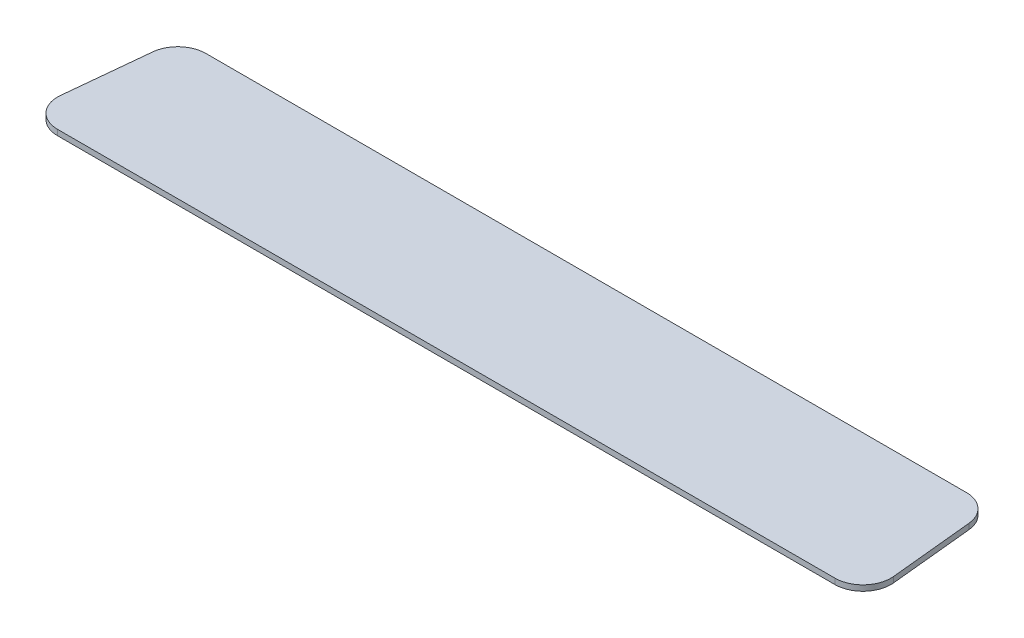
SolidWorks part; units mm, degrees
ref_plane "Front Plane" through (0, 0, 0) normal (0, 0, 1) x (1, 0, 0)
ref_plane "Top Plane" through (0, 0, 0) normal (0, 1, 0) x (1, 0, 0)
ref_plane "Right Plane" through (0, 0, 0) normal (1, 0, 0) x (0, 0, -1)
sketch "Sketch3" plane through (0, 0, 0) normal (0, 1, 0) x (1, 0, 0)
  line L0 (-138.9501, 0) -> (138.9501, 0)
  line L1 (-135.9501, 50) -> (135.9501, 50)
  line L2 (-145.9005, 40.995) -> (-148.9005, 10.995)
  line L3 (145.9005, 40.995) -> (148.9005, 10.995)
  arc A0 (138.9501, 0) -> (148.9005, 10.995) centre (138.9501, 10) ccw
  arc A1 (135.9501, 50) -> (145.9005, 40.995) centre (135.9501, 40) cw
  arc A2 (-138.9501, 0) -> (-148.9005, 10.995) centre (-138.9501, 10) cw
  arc A3 (-135.9501, 50) -> (-145.9005, 40.995) centre (-135.9501, 40) ccw
  point P4 (0, 0)
  point P8 (0, 50)
  point P10 (150, 0)
  point P13 (145, 50)
  point P16 (-150, 0)
  point P19 (-145, 50)
  dimension "D4" = 10
  dimension "D1" = 300
  dimension "D2" = 290
  dimension "D3" = 50
extrude "Boss-Extrude1" add sketch "Sketch3" along normal blind 2
